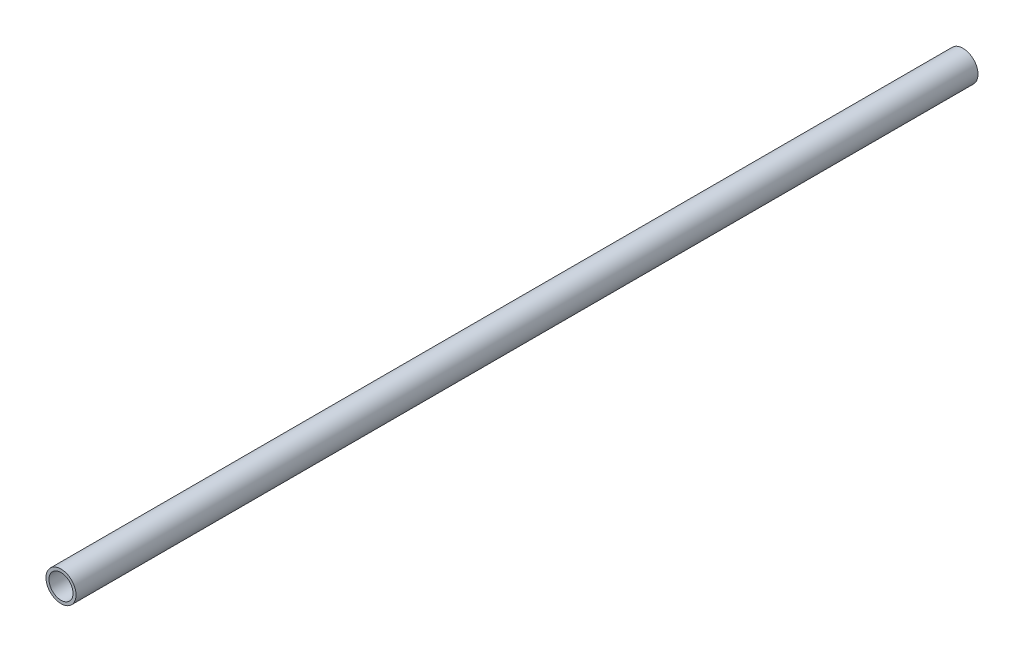
SolidWorks part; units mm, degrees
material "EM-CF"
ref_plane "Płaszczyzna przednia" through (0, 0, 0) normal (0, 0, 1) x (1, 0, 0)
ref_plane "Płaszczyzna górna" through (0, 0, 0) normal (0, 1, 0) x (1, 0, 0)
ref_plane "Płaszczyzna prawa" through (0, 0, 0) normal (1, 0, 0) x (0, 0, -1)
sketch "Szkic1" plane through (0, 0, 0) normal (0, 0, 1) x (1, 0, 0)
  circle A0 centre (0, 0) radius 4
  circle A1 centre (0, 0) radius 5
  dimension "D1" = 1
  dimension "D2" = 10
extrude "Dodanie-wyciągnięcie1" add sketch "Szkic1" along normal blind 300
